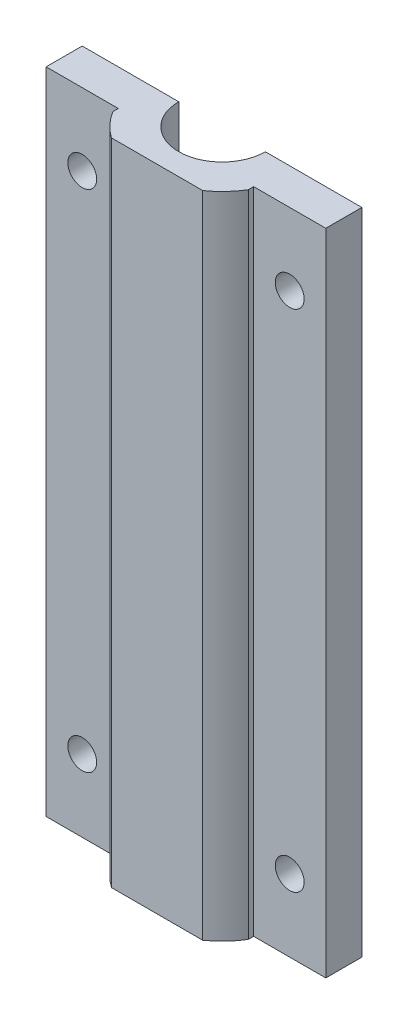
SolidWorks part; units mm, degrees
ref_plane "Ebene vorne" through (0, 0, 0) normal (0, 0, 1) x (1, 0, 0)
ref_plane "Ebene oben" through (0, 0, 0) normal (0, 1, 0) x (1, 0, 0)
ref_plane "Ebene rechts" through (0, 0, 0) normal (1, 0, 0) x (0, 0, -1)
sketch "Skizze3" plane through (0, 0, 0) normal (0, 0, 1) x (1, 0, 0)
  line L0 (0, 0) -> (-11, 0)
  line L1 (-11, 0) -> (-11, 90)
  line L2 (-11, 90) -> (-6, 90)
  line L3 (-6, 90) -> (-6, 10)
  line L4 (-6, 10) -> (0, 10)
  line L5 (0, 10) -> (0, 0)
  line L6 (0, 0) -> (0, 91.7062) construction
  dimension "D1" = 90
  dimension "D2" = 11
  dimension "D3" = 80
  dimension "D4" = 5
revolve "Rotation1" add sketch "Skizze3" angle 180 about L6
sketch "Skizze6" plane through (0, 90, 0) normal (0, 1, 0) x (1, 0, 0)
  line L0 (-9.3806, -5.7449) -> (-9.3806, 0)
  line L1 (-6, 0) -> (-11, 0) construction
  arc A0 (-11, 0) -> (11, 0) centre (0, 0) ccw construction
extrude "Schnitt-Linear austragen2" cut sketch "Skizze6" against normal blind 90 and the other way through all
sketch "Skizze7" plane through (0, 0, 0) normal (0, -1, 0) x (1, 0, 0)
  line L1 (9.3806, 5.7449) -> (9.3806, 0)
  line L2 (11, 0) -> (-9.3806, 0) construction
  arc A0 (11, 0) -> (-9.3806, 5.7449) centre (0, 0) ccw construction
extrude "Schnitt-Linear austragen3" cut sketch "Skizze7" against normal blind 90 and the other way through all
sketch "Skizze8" plane through (0, 90, 0) normal (0, 1, 0) x (1, 0, 0)
  line L1 (-9.3806, 0) -> (-19.3806, 0)
  line L2 (-9.3806, 0) -> (-9.3806, -5)
  line L3 (-9.3806, -5) -> (-19.3806, -5)
  line L4 (-19.3806, 0) -> (-19.3806, -5)
  dimension "D1" = 10
  dimension "D2" = 5
extrude "Aufsatz-Linear austragen2" add sketch "Skizze8" against normal blind 90
sketch "Skizze9" plane through (0, 90, 0) normal (0, 1, 0) x (1, 0, 0)
  line L1 (9.3806, 0) -> (19.3806, 0)
  line L2 (9.3806, 0) -> (9.3806, -5)
  line L3 (9.3806, -5) -> (19.3806, -5)
  line L4 (19.3806, 0) -> (19.3806, -5)
  dimension "D1" = 10
  dimension "D2" = 5
extrude "Aufsatz-Linear austragen3" add sketch "Skizze9" against normal blind 90
sketch "Skizze14" plane through (0, 0, 5) normal (0, 0, 1) x (1, 0, 0)
  line L0 (-19.3806, 0) -> (-19.3806, 90) construction
  line L1 (19.3806, 0) -> (19.3806, 90) construction
  line L2 (-19.3806, 90) -> (-9.3806, 90) construction
  line L3 (9.3806, 90) -> (19.3806, 90) construction
  line L4 (9.3806, 0) -> (19.3806, 0) construction
  line L5 (-19.3806, 0) -> (-9.3806, 0) construction
  circle A0 centre (-14.3806, 80) radius 2
  circle A1 centre (-14.3806, 10) radius 2
  circle A2 centre (14.3806, 10) radius 2
  circle A3 centre (14.3806, 80) radius 2
  dimension "D1" = 4
  dimension "D2" = 4
  dimension "D3" = 4
  dimension "D4" = 4
  dimension "D5" = 5
  dimension "D6" = 5
  dimension "D7" = 5
  dimension "D8" = 5
  dimension "D9" = 10
  dimension "D10" = 10
  dimension "D11" = 10
  dimension "D12" = 10
extrude "Schnitt-Linear austragen7" cut sketch "Skizze14" against normal through all
sketch "Skizze15" plane through (0, 0, 0) normal (0, 0, -1) x (-1, 0, 0)
  line L0 (0, 10) -> (0, 0) construction
  line L1 (6, 10) -> (-6, 10) construction
sketch "Skizze16" plane through (0, 0, 0) normal (0, -1, 0) x (1, 0, 0)
  circle A0 centre (0, 0) radius 1
  dimension "D1" = 2
extrude "Schnitt-Linear austragen8" cut sketch "Skizze16" against normal through all
sketch "Skizze18" plane through (0, 0, 0) normal (0, -1, 0) x (1, 0, 0)
  circle A0 centre (0, 0) radius 4
  dimension "D1" = 8
extrude "Schnitt-Linear austragen9" cut sketch "Skizze18" against normal blind 5
sketch "Skizze13" plane through (0, 0, 0) normal (0, -1, 0) x (1, 0, 0)
  circle A0 centre (0, 0) radius 4
  dimension "D1" = 8
sketch "Skizze20" plane through (0, 90, 0) normal (0, 1, 0) x (1, 0, 0)
  line L1 (10.4001, -11) -> (-11.3005, -11)
  line L2 (10.4001, -11) -> (10.4001, -9)
  line L3 (10.4001, -9) -> (-11.3005, -9)
  line L4 (-11.3005, -11) -> (-11.3005, -9)
  dimension "D1" = 2
extrude "Schnitt-Linear austragen10" cut sketch "Skizze20" against normal through all
